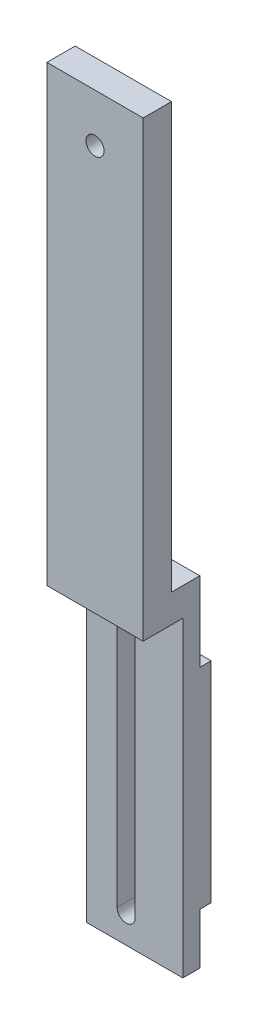
SolidWorks part; units mm, degrees
ref_plane "Front Plane" through (0, 0, 0) normal (0, 0, 1) x (1, 0, 0)
ref_plane "Top Plane" through (0, 0, 0) normal (0, 1, 0) x (1, 0, 0)
ref_plane "Right Plane" through (0, 0, 0) normal (1, 0, 0) x (0, 0, -1)
sketch "Sketch1" plane through (0, 0, 0) normal (0, 0, 1) x (1, 0, 0)
  line L0 (-1.5, 20) -> (-1.5, -25) construction
  line L1 (-8.5, -30) -> (8.5, -30)
  line L2 (-8.5, -30) -> (-8.5, 30)
  line L3 (-8.5, 30) -> (8.5, 30)
  line L4 (8.5, -30) -> (8.5, 30)
  line L5 (-8.5, -30) -> (8.5, 30) construction
  line L6 (-8.5, 30) -> (8.5, -30) construction
  line L7 (-8.5, -30) -> (8.5, -30)
  line L8 (0.1, 20) -> (0.1, -25)
  line L9 (-3.1, 20) -> (-3.1, -25)
  arc A0 (0.1, 20) -> (-3.1, 20) centre (-1.5, 20) ccw
  arc A1 (-3.1, -25) -> (0.1, -25) centre (-1.5, -25) ccw
  point P0 (0, 0)
  point P8 (-1.5, -2.5)
  dimension "D2" = 7
  dimension "D5" = 25
  dimension "D4" = 1.6
  dimension "D1" = 60
  dimension "D3" = 17
  dimension "D6" = 20
extrude "Boss-Extrude1" add sketch "Sketch1" along normal blind 5
sketch "Sketch2" plane through (0, 0, 5) normal (0, 0, 1) x (1, 0, 0)
  line L0 (8.5, -30) -> (8.5, 30) construction
  line L1 (-8.5, 30) -> (8.5, 30)
  line L2 (-8.5, 30) -> (-8.5, 25)
  line L3 (-8.5, 25) -> (8.5, 25)
  line L4 (8.5, 30) -> (8.5, 25)
  dimension "D1" = 5
extrude "Boss-Extrude2" add sketch "Sketch2" along normal blind 7
sketch "Sketch3" plane through (0, 30, 0) normal (0, 1, 0) x (1, 0, 0)
  line L0 (-8.5, -12) -> (-8.5, 0) construction
  line L1 (8.5, -12) -> (-8.5, -12)
  line L2 (8.5, -12) -> (8.5, -7)
  line L3 (8.5, -7) -> (-8.5, -7)
  line L4 (-8.5, -12) -> (-8.5, -7)
  dimension "D1" = 5
extrude "Boss-Extrude3" add sketch "Sketch3" along normal blind 75
sketch "Sketch4" plane through (0, 0, 7) normal (0, 0, -1) x (-1, 0, 0)
  line L3 (-8.5, 105) -> (8.5, 105) construction
  circle A2 centre (0, 96.5) radius 1.6
  point P10 (0, 105)
  dimension "D1" = 3.2
  dimension "D2" = 8.5
extrude "Cut-Extrude1" cut sketch "Sketch4" against normal through all
sketch "Sketch5" plane through (0, 0, 0) normal (0, 0, -1) x (-1, 0, 0)
  line L0 (8.5, 30) -> (-8.5, 30) construction
  line L1 (-0.5, 30) -> (-8.5, 30)
  line L2 (-0.5, 30) -> (-0.5, 16)
  line L3 (-0.5, 16) -> (-8.5, 16)
  line L4 (-8.5, 30) -> (-8.5, 16)
  line L5 (-0.5, 30) -> (-8.5, 16) construction
  line L6 (-0.5, 16) -> (-8.5, 30) construction
  line L7 (-0.5, -21) -> (-0.1, -21)
  line L8 (8.5, -30) -> (8.5, 30) construction
  line L9 (-8.5, -30) -> (-8.5, 30) construction
  line L10 (-0.1, 20) -> (-0.1, -25) construction
  line L11 (-0.1, 20) -> (-0.1, -25)
  line L12 (-0.5, 16) -> (-0.1, 16)
  line L13 (1.5, 21.6) -> (-0.5, 21.6)
  line L14 (-8.5, -30) -> (-0.5, -30)
  line L15 (-8.5, -30) -> (-8.5, -21)
  line L16 (-8.5, -21) -> (-0.5, -21)
  line L17 (-0.5, -30) -> (-0.5, -21)
  line L18 (-8.5, -30) -> (-0.5, -21) construction
  line L19 (-8.5, -21) -> (-0.5, -30) construction
  line L20 (1.5, -26.6) -> (-0.5, -26.6)
  arc A0 (3.1, 20) -> (-0.1, 20) centre (1.5, 20) ccw construction
  arc A1 (3.1, 20) -> (-0.1, 20) centre (1.5, 20) ccw
  arc A2 (-0.1, -25) -> (3.1, -25) centre (1.5, -25) ccw construction
  arc A3 (-0.1, -25) -> (3.1, -25) centre (1.5, -25) ccw
  point P4 (-4.5, 23)
  point P22 (-4.5, -25.5)
  arc M5 (3.1, -25) -> (-0.1, -25) centre (1.5, -25) cw
  line M6 (-0.1, -25) -> (-0.1, 20)
  arc M7 (-0.1, 20) -> (3.1, 20) centre (1.5, 20) cw
  line M9 (-8.5, -30) -> (8.5, -30)
  line M11 (8.5, 30) -> (-8.5, 30)
  line M12 (-8.5, 30) -> (-8.5, -30)
  dimension "D1" = 14
  dimension "D2" = 9
  dimension "D3" = 9
extrude "Cut-Extrude2" cut sketch "Sketch5" against normal blind 2 contours L3 L2 M11 M12 | L13 L2 L12 L11 M7 | L17 L16 M9 M12 | L20 L7 L17 M5 M6
